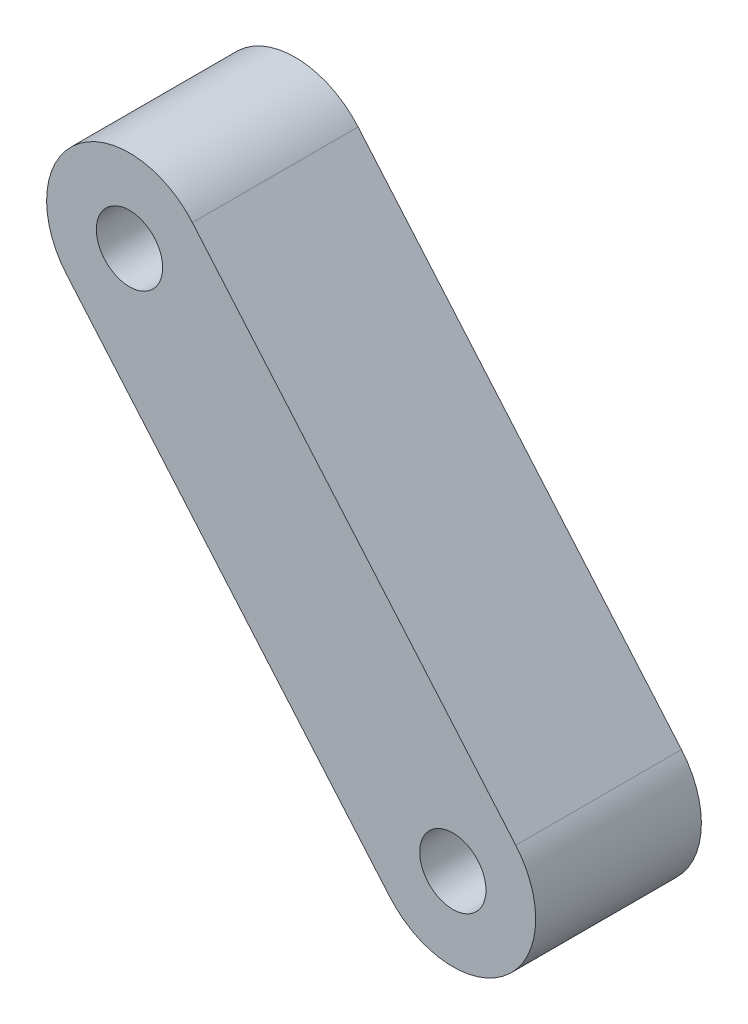
SolidWorks part; units mm, degrees
ref_plane "Front Plane" through (0, 0, 0) normal (0, 0, 1) x (1, 0, 0)
ref_plane "Top Plane" through (0, 0, 0) normal (0, 1, 0) x (1, 0, 0)
ref_plane "Right Plane" through (0, 0, 0) normal (1, 0, 0) x (0, 0, -1)
sketch "Sketch1" plane through (0, 0, 0) normal (0, 0, 1) x (1, 0, 0)
  line L48 (42.2025, 6.7475) -> (22.6873, 29.5324)
  line L49 (49.7975, 13.2525) -> (30.2822, 36.0375)
  arc A11 (30.2822, 36.0375) -> (22.6873, 29.5324) centre (26.4848, 32.785) ccw
  arc A12 (42.2025, 6.7475) -> (49.7975, 13.2525) centre (46, 10) ccw
  circle A13 centre (26.4848, 32.785) radius 2
  circle A14 centre (46, 10) radius 2
  dimension "D4" = 30
extrude "Boss-Extrude1" add sketch "Sketch1" along normal blind 10
